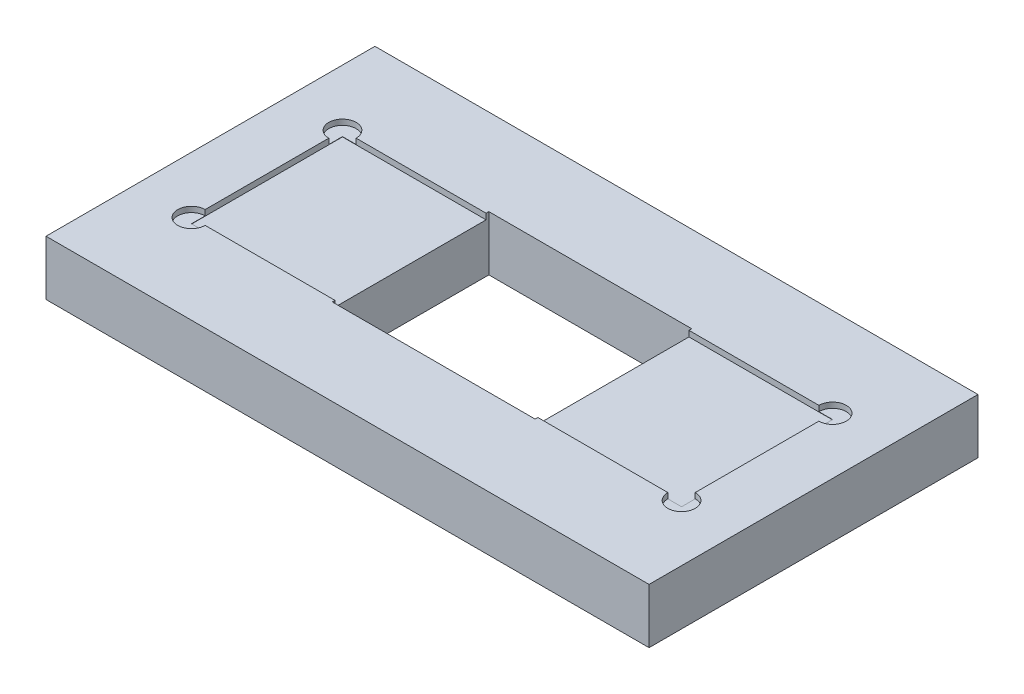
SolidWorks part; units mm, degrees
material "Plain Carbon Steel"
ref_plane "Front Plane" through (0, 0, 0) normal (0, 0, 1) x (1, 0, 0)
ref_plane "Top Plane" through (0, 0, 0) normal (0, 1, 0) x (1, 0, 0)
ref_plane "Right Plane" through (0, 0, 0) normal (1, 0, 0) x (0, 0, -1)
sketch "Sketch1" plane through (0, 0, 0) normal (0, 1, 0) x (1, 0, 0)
  line L1 (-110, -60) -> (110, -60)
  line L2 (-110, -60) -> (-110, 60)
  line L3 (-110, 60) -> (110, 60)
  line L4 (110, -60) -> (110, 60)
  line L5 (-110, -60) -> (110, 60) construction
  line L6 (-110, 60) -> (110, -60) construction
  point P0 (0, 0)
  dimension "D1" = 220
  dimension "D2" = 120
extrude "Boss-Extrude1" add sketch "Sketch1" against normal blind 20
sketch "Sketch2" plane through (0, 0, 0) normal (0, 1, 0) x (1, 0, 0)
  line L1 (-89.4, -27.55) -> (89.4, -27.55)
  line L2 (-89.4, -27.55) -> (-89.4, 27.55)
  line L3 (-89.4, 27.55) -> (89.4, 27.55)
  line L4 (89.4, -27.55) -> (89.4, 27.55)
  line L5 (-89.4, -27.55) -> (89.4, 27.55) construction
  line L6 (-89.4, 27.55) -> (89.4, -27.55) construction
  point P0 (0, 0)
  dimension "D1" = 178.8
  dimension "D2" = 55.1
extrude "Cut-Extrude1" cut sketch "Sketch2" against normal blind 2.1
sketch "Sketch3" plane through (0, 0, 0) normal (0, 1, 0) x (1, 0, 0)
  circle A0 centre (-89.4, 27.55) radius 5
  circle A1 centre (89.4, 27.55) radius 5
  circle A2 centre (89.4, -27.55) radius 5
  circle A3 centre (-89.4, -27.55) radius 5
  dimension "D1" = 10
extrude "Cut-Extrude2" cut sketch "Sketch3" against normal blind 2
sketch "Sketch4" plane through (0, -2.1, 0) normal (0, 1, 0) x (1, 0, 0)
  line L1 (-37, -28.55) -> (37, -28.55)
  line L2 (-37, -28.55) -> (-37, 28.55)
  line L3 (-37, 28.55) -> (37, 28.55)
  line L4 (37, -28.55) -> (37, 28.55)
  line L6 (89.4, 27.55) -> (-89.4, 27.55) construction
  line L7 (-84.4, -27.55) -> (84.4, -27.55) construction
  point P8 (0, -28.55)
  dimension "D1" = 74
  dimension "D2" = 1
  dimension "D3" = 1
extrude "Cut-Extrude3" cut sketch "Sketch4" against normal through all both and the other way through all
sketch "Sketch5" plane through (0, -20, 0) normal (0, -1, 0) x (1, 0, 0)
  line L1 (55, -37.5) -> (-55, -37.5) construction
  line L2 (55, -37.5) -> (55, 37.5) construction
  line L3 (55, 37.5) -> (-55, 37.5) construction
  line L4 (-55, -37.5) -> (-55, 37.5) construction
  line L5 (55, -37.5) -> (-55, 37.5) construction
  line L6 (55, 37.5) -> (-55, -37.5) construction
  circle A0 centre (-55, 37.5) radius 5
  circle A1 centre (55, 37.5) radius 5
  circle A2 centre (55, -37.5) radius 5
  circle A3 centre (-55, -37.5) radius 5
  point P0 (0, 0)
  dimension "D3" = 10
  dimension "D1" = 75
  dimension "D2" = 110
